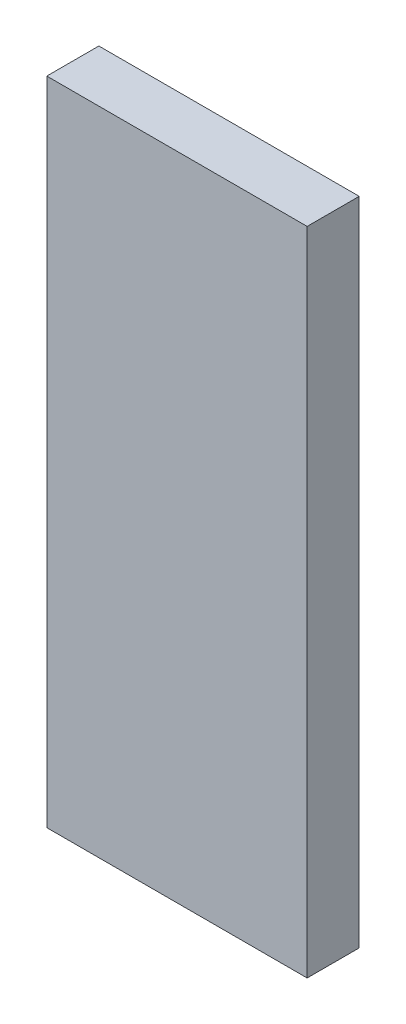
SolidWorks part; units mm, degrees
ref_plane "Front Plane" through (0, 0, 0) normal (0, 0, 1) x (1, 0, 0)
ref_plane "Top Plane" through (0, 0, 0) normal (0, 1, 0) x (1, 0, 0)
ref_plane "Right Plane" through (0, 0, 0) normal (1, 0, 0) x (0, 0, -1)
sketch "Sketch1" plane through (0, 0, 0) normal (0, 1, 0) x (1, 0, 0)
  line L1 (-20, 4) -> (20, 4)
  line L2 (-20, 4) -> (-20, -4)
  line L3 (-20, -4) -> (20, -4)
  line L4 (20, 4) -> (20, -4)
  line L5 (-20, 4) -> (20, -4) construction
  line L6 (-20, -4) -> (20, 4) construction
  point P0 (0, 0)
  dimension "D1" = 40
  dimension "D2" = 8
extrude "Boss-Extrude1" add sketch "Sketch1" along normal blind 100
